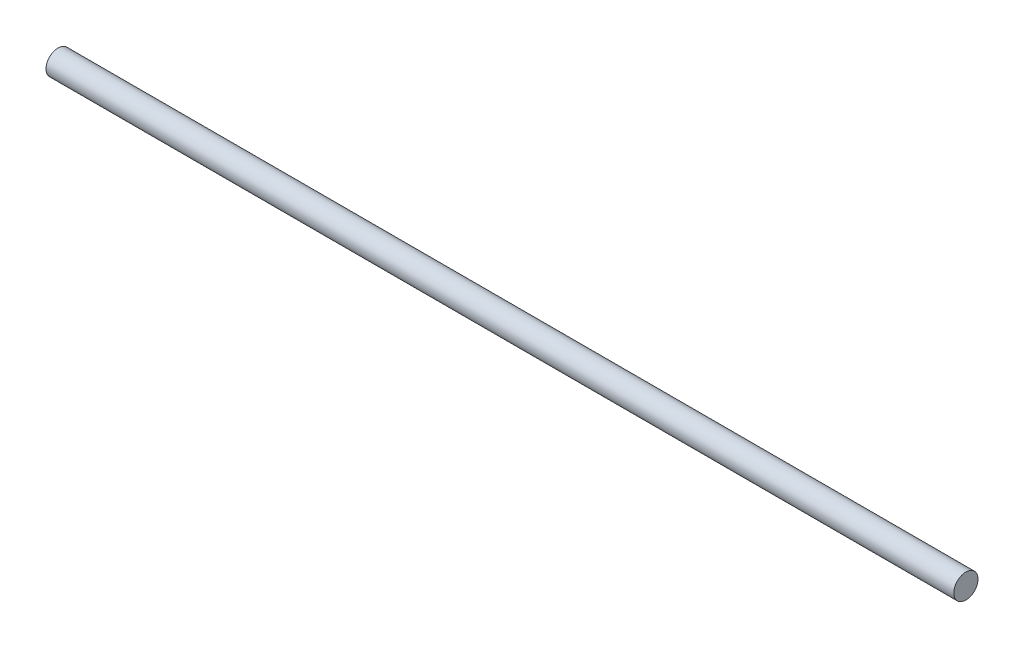
SolidWorks part; units mm, degrees
ref_plane "Front Plane" through (0, 0, 0) normal (0, 0, 1) x (1, 0, 0)
ref_plane "Top Plane" through (0, 0, 0) normal (0, 1, 0) x (1, 0, 0)
ref_plane "Right Plane" through (0, 0, 0) normal (1, 0, 0) x (0, 0, -1)
sketch "Sketch1" plane through (0, 0, 0) normal (1, 0, 0) x (0, 0, -1)
  circle A0 centre (0, 0) radius 6.35
  dimension "D1" = 12.7
extrude "Boss-Extrude1" add sketch "Sketch1" along normal blind 474.8
